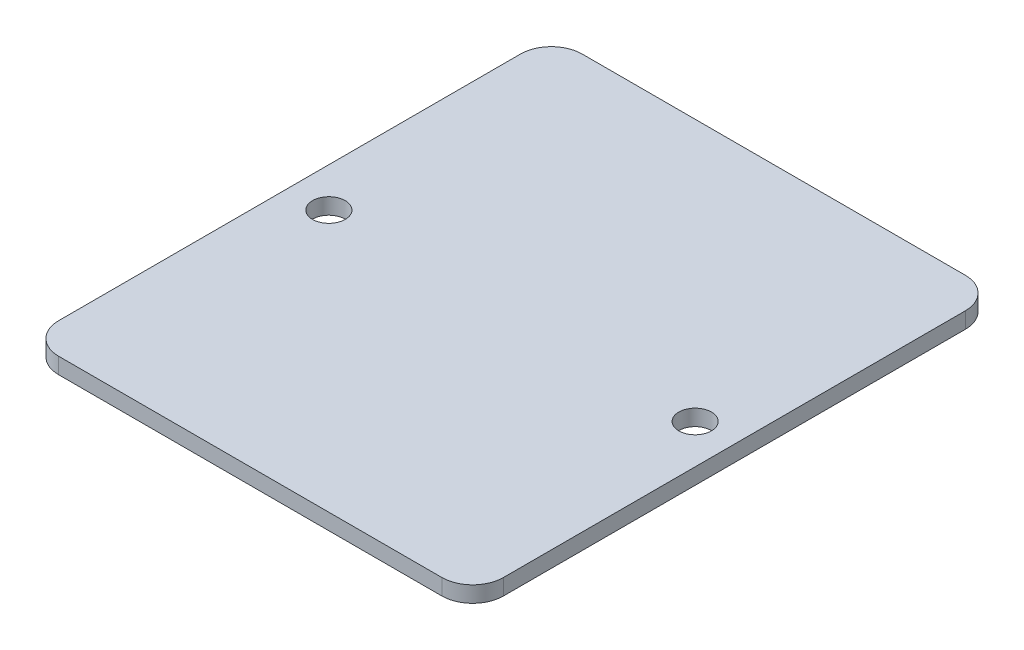
SolidWorks part; units mm, degrees
material "PVC 0.007 Plasticized"
ref_plane "Front Plane" through (0, 0, 0) normal (0, 0, 1) x (1, 0, 0)
ref_plane "Top Plane" through (0, 0, 0) normal (0, 1, 0) x (1, 0, 0)
ref_plane "Right Plane" through (0, 0, 0) normal (1, 0, 0) x (0, 0, -1)
sketch "Sketch1" plane through (0, 0, 0) normal (0, 1, 0) x (1, 0, 0)
  line L1 (-21.625, 25.45) -> (21.625, 25.45)
  line L2 (-21.625, 25.45) -> (-21.625, -25.45)
  line L3 (-21.625, -25.45) -> (21.625, -25.45)
  line L4 (21.625, 25.45) -> (21.625, -25.45)
extrude "Boss-Extrude1" add sketch "Sketch1" along normal blind 1.56
fillet "Fillet1" radius 3 1 edges at (21.625, 0.78, 25.45)
fillet "Fillet2" radius 3 3 edges at (-21.625, 0.78, -25.45) (-21.625, 0.78, 25.45) (21.625, 0.78, -25.45)
sketch "Sketch2" plane through (0, 1.56, 0) normal (0, 1, 0) x (1, 0, 0)
  circle A0 centre (-17.805, 0) radius 1.5875
  circle A1 centre (17.805, 0) radius 1.5875
extrude "Cut-Extrude1" cut sketch "Sketch2" against normal blind 1.56
